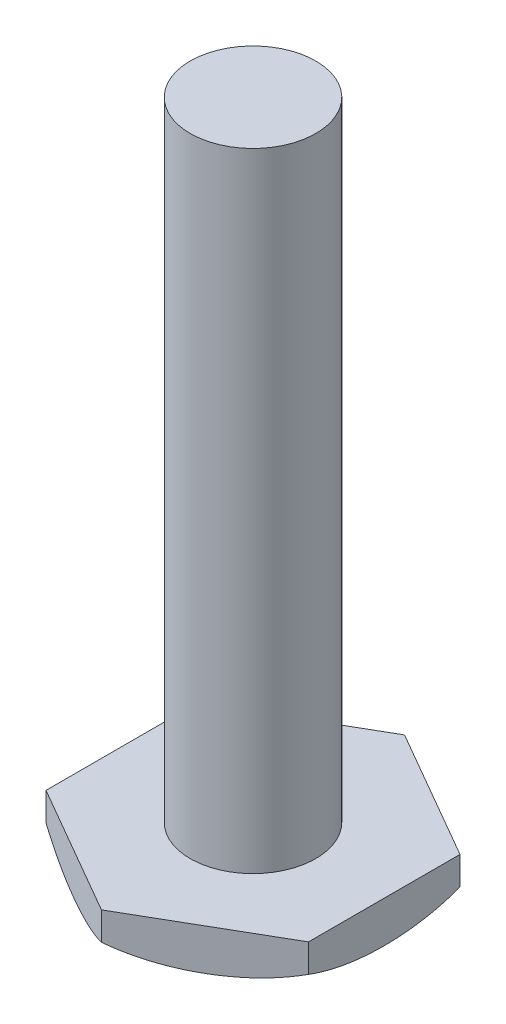
SolidWorks part; units mm, degrees
material "AISI 1020"
ref_plane "Front Plane" through (0, 0, 0) normal (0, 0, 1) x (1, 0, 0)
ref_plane "Top Plane" through (0, 0, 0) normal (0, 1, 0) x (1, 0, 0)
ref_plane "Right Plane" through (0, 0, 0) normal (1, 0, 0) x (0, 0, -1)
sketch "Sketch1" plane through (0, 0, 0) normal (0, 0, 1) x (1, 0, 0)
  line L0 (13.9454, -14.1868) -> (13.9454, -1.1012)
  line L1 (13.9454, 49.3132) -> (20.2954, 49.3132)
  line L3 (4.9729, -14.1868) -> (13.9454, -14.1868)
  line L5 (20.2954, -18.5556) -> (7.4133, -18.5556)
  line L6 (4.9729, -17.0316) -> (4.9729, -14.1868)
  line L12 (20.2954, 49.3132) -> (20.2954, -18.5556)
  line L14 (13.9454, -1.1012) -> (13.9454, 49.3132)
  arc A5 (4.9729, -17.0316) -> (7.4133, -18.5556) centre (14.4799, -4.524) ccw
revolve "Revolve1" add sketch "Sketch1" angle 360 about L12
sketch "Sketch2" plane through (0, -18.5556, 0) normal (0, -1, 0) x (1, 0, 0)
  line L1 (20.2954, 15.322) -> (7.0262, 7.661)
  line L2 (7.0262, 7.661) -> (7.0262, -7.661)
  line L3 (7.0262, -7.661) -> (20.2954, -15.322)
  line L4 (20.2954, -15.322) -> (33.5647, -7.661)
  line L5 (33.5647, -7.661) -> (33.5647, 7.661)
  line L6 (33.5647, 7.661) -> (20.2954, 15.322)
extrude "Cut-Extrude1" cut sketch "Sketch2" against normal through all flip side to cut
